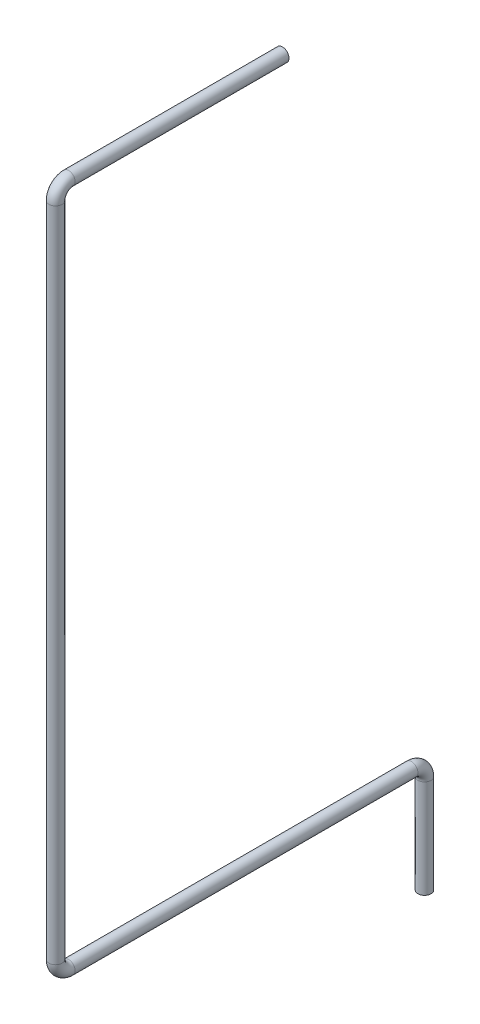
SolidWorks part; units mm, degrees
ref_plane "Alzado" through (0, 0, 0) normal (0, 0, 1) x (1, 0, 0)
ref_plane "Planta" through (0, 0, 0) normal (0, 1, 0) x (1, 0, 0)
ref_plane "Vista lateral" through (0, 0, 0) normal (1, 0, 0) x (0, 0, -1)
sketch "Croquis1" plane through (0, 0, 0) normal (1, 0, 0) x (0, 0, -1)
  line L0 (0, 0) -> (-32.66, 0)
  line L1 (-34.66, -2) -> (-34.66, -102.36)
  line L2 (-32.66, -104.36) -> (19.69, -104.36)
  line L3 (21.69, -106.36) -> (21.69, -121.36)
  arc A0 (-34.66, -2) -> (-32.66, 0) centre (-32.66, -2) cw
  arc A1 (-32.66, -104.36) -> (-34.66, -102.36) centre (-32.66, -102.36) cw
  arc A2 (21.69, -106.36) -> (19.69, -104.36) centre (19.69, -106.36) ccw
  point P8 (-34.66, 0)
  point P11 (-34.66, -104.36)
  point P14 (21.69, -104.36)
  dimension "D5" = 2
  dimension "D6" = 2
  dimension "D7" = 2
  dimension "D1" = 34.66
  dimension "D2" = 104.36
  dimension "D3" = 56.35
  dimension "D4" = 17
sweep "Barrer1" add path "Croquis1" circular profile diameter 2 parameters "D3"=2
